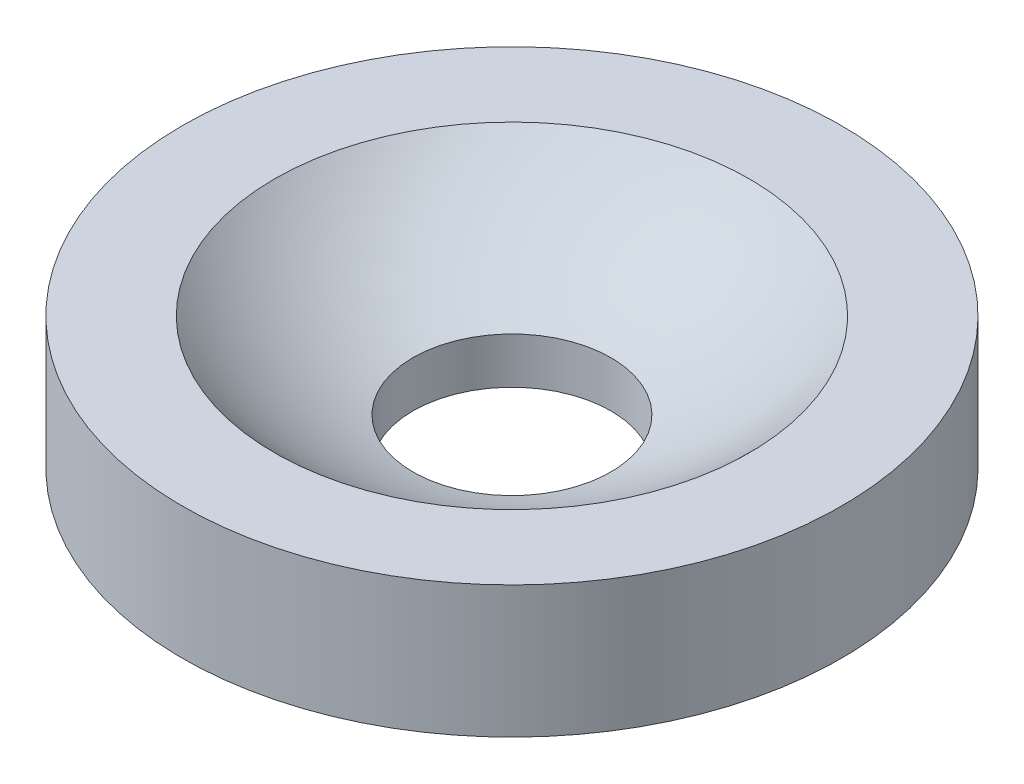
SolidWorks part; units mm, degrees
ref_plane "前视基准面" through (0, 0, 0) normal (0, 0, 1) x (1, 0, 0)
ref_plane "上视基准面" through (0, 0, 0) normal (0, 1, 0) x (1, 0, 0)
ref_plane "右视基准面" through (0, 0, 0) normal (1, 0, 0) x (0, 0, -1)
sketch "草图1" plane through (0, 0, 0) normal (0, 0, 1) x (1, 0, 0)
  line L0 (0, 0) -> (0, -11.4623) construction
  line L1 (3.5, 2) -> (5, 2)
  line L2 (5, 2) -> (5, 0)
  line L3 (5, 0) -> (1.5021, 0)
  line L4 (1.5021, 0) -> (1.5021, 0.7)
  line L5 (3.5, 2) -> (1.5021, 0.7)
  dimension "D1" = 3.5
  dimension "D2" = 1.3
  dimension "D3" = 2
  dimension "D4" = 1.5021
  dimension "D5" = 5
revolve "旋转1" add sketch "草图1" angle 360 about L0
sketch "草图2" plane through (0, 0, 0) normal (0, 0, 1) x (1, 0, 0)
  line L0 (0, 0) -> (0, 5.469) construction
  line L1 (0, 0.469) -> (0, 10.469)
  arc A0 (0, 0.469) -> (0, 10.469) centre (0, 5.469) ccw
  dimension "D1" = 10
revolve "切除-旋转2" cut sketch "草图2" angle 360 about L0
